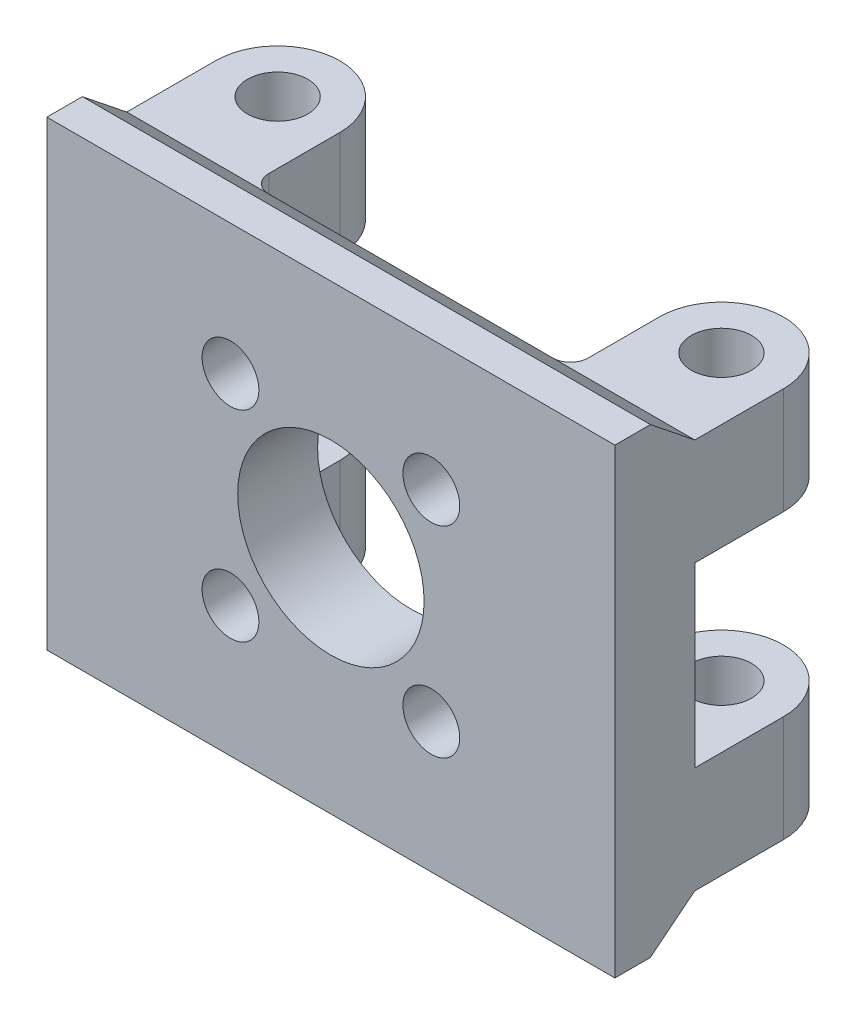
SolidWorks part; units mm, degrees
ref_plane "前视基准面" through (0, 0, 0) normal (0, 0, 1) x (1, 0, 0)
ref_plane "上视基准面" through (0, 0, 0) normal (0, 1, 0) x (1, 0, 0)
ref_plane "右视基准面" through (0, 0, 0) normal (1, 0, 0) x (0, 0, -1)
other "Configuration Table"
ref_plane "基准面1" through (0, 0, 0) normal (0, 0, -1) x (-1, 0, 0)
sketch "草图1" plane through (0, 0, 0) normal (0, 0, -1) x (-1, 0, 0)
  line L0 (16, 11) -> (-16, 11)
  line L1 (-16, 11) -> (-16, -11)
  line L2 (-16, -11) -> (16, -11)
  line L3 (16, -11) -> (16, 11)
extrude "凸台-拉伸1" add sketch "草图1" against normal blind 2.5
ref_plane "基准面2" through (0, 11, 0) normal (0, 1, 0) x (1, 0, 0)
sketch "草图2" plane through (0, 11, 0) normal (0, 1, 0) x (1, 0, 0)
  line L0 (9, 5) -> (9, 1)
  line L1 (8, 0) -> (16, 0)
  line L2 (16, 0) -> (16, 5)
  arc A0 (16, 5) -> (9, 5) centre (12.5, 5) ccw
  arc A1 (9, 1) -> (8, 0) centre (8, 1) cw
extrude "凸台-拉伸2" add sketch "草图2" against normal blind 6
sketch "草图3" plane through (0, 11, 0) normal (0, 1, 0) x (1, 0, 0)
  line L0 (-16, 0) -> (-8, 0)
  line L1 (-9, 1) -> (-9, 5)
  line L2 (-16, 5) -> (-16, 0)
  arc A0 (-8, 0) -> (-9, 1) centre (-8, 1) cw
  arc A1 (-9, 5) -> (-16, 5) centre (-12.5, 5) ccw
extrude "凸台-拉伸3" add sketch "草图3" against normal blind 6
ref_plane "基准面3" through (0, -11, 0) normal (0, -1, 0) x (1, 0, 0)
sketch "草图4" plane through (0, -11, 0) normal (0, -1, 0) x (1, 0, 0)
  line L0 (-8, 0) -> (-16, 0)
  line L1 (-16, 0) -> (-16, -5)
  line L2 (-9, -5) -> (-9, -1)
  arc A0 (-16, -5) -> (-9, -5) centre (-12.5, -5) ccw
  arc A1 (-9, -1) -> (-8, 0) centre (-8, -1) cw
extrude "凸台-拉伸4" add sketch "草图4" against normal blind 6
sketch "草图5" plane through (0, -11, 0) normal (0, -1, 0) x (1, 0, 0)
  line L0 (16, -5) -> (16, 0)
  line L1 (16, 0) -> (8, 0)
  line L2 (9, -1) -> (9, -5)
  arc A0 (9, -5) -> (16, -5) centre (12.5, -5) ccw
  arc A1 (8, 0) -> (9, -1) centre (8, -1) cw
extrude "凸台-拉伸5" add sketch "草图5" against normal blind 6
hole_wizard "Ø3.4 (3.4) 直径孔1" positions "草图7" profile "草图6" hole size "Ø3.4" standard "ANSI Metric"
sketch "草图7" plane through (0, -5, 0) normal (0, 1, 0) x (1, 0, 0)
  point P0 (-12.5, 5)
sketch "草图6" plane through (-12.5, -5, -5) normal (1, 0, 0) x (0, 0, 1)
  line L0 (0, 0) -> (0, 6)
  line L1 (0, 6) -> (1.7, 6)
  line L2 (1.7, 6) -> (1.7, 0)
  line L5 (1.7, 0) -> (0, 0)
  line L11 (0, -6.35) -> (0, 107.95) construction
  dimension "通孔孔直径" = 3.4
  dimension "通孔孔深度" = 6
hole_wizard "Ø3.4 (3.4) 直径孔2" positions "草图9" profile "草图8" hole size "Ø3.4" standard "ANSI Metric"
sketch "草图9" plane through (0, -11, 0) normal (0, -1, 0) x (-1, 0, 0)
  point P0 (-12.5, 5)
sketch "草图8" plane through (12.5, -11, -5) normal (1, 0, 0) x (0, 0, -1)
  line L0 (0, 0) -> (0, 6)
  line L1 (0, 6) -> (1.7, 6)
  line L2 (1.7, 6) -> (1.7, 0)
  line L5 (1.7, 0) -> (0, 0)
  line L11 (0, -6.35) -> (0, 107.95) construction
  dimension "通孔孔直径" = 3.4
  dimension "通孔孔深度" = 6
hole_wizard "Ø3.4 (3.4) 直径孔3" positions "草图11" profile "草图10" hole size "Ø3.4" standard "ANSI Metric"
sketch "草图11" plane through (0, 5, 0) normal (0, -1, 0) x (-1, 0, 0)
  point P0 (12.5, 5)
sketch "草图10" plane through (-12.5, 5, -5) normal (1, 0, 0) x (0, 0, -1)
  line L0 (0, 0) -> (0, 6)
  line L1 (0, 6) -> (1.7, 6)
  line L2 (1.7, 6) -> (1.7, 0)
  line L5 (1.7, 0) -> (0, 0)
  line L11 (0, -6.35) -> (0, 107.95) construction
  dimension "通孔孔直径" = 3.4
  dimension "通孔孔深度" = 6
hole_wizard "Ø3.4 (3.4) 直径孔4" positions "草图13" profile "草图12" hole size "Ø3.4" standard "ANSI Metric"
sketch "草图13" plane through (0, 11, 0) normal (0, 1, 0) x (1, 0, 0)
  point P0 (12.5, 5)
sketch "草图12" plane through (12.5, 11, -5) normal (1, 0, 0) x (0, 0, 1)
  line L0 (0, 0) -> (0, 22)
  line L1 (0, 22) -> (1.7, 22)
  line L2 (1.7, 22) -> (1.7, 0)
  line L5 (1.7, 0) -> (0, 0)
  line L11 (0, -6.35) -> (0, 107.95) construction
  dimension "通孔孔直径" = 3.4
  dimension "通孔孔深度" = 22
hole_wizard "Ø3.2 (3.2) 直径孔1" positions "草图15" profile "草图14" hole size "Ø3.2" standard "ANSI Metric"
sketch "草图15" plane through (0, 0, 0) normal (0, 0, -1) x (-1, 0, 0)
  point P0 (5.6569, 5.6569)
  point P1 (-5.6569, 5.6569)
  point P2 (-5.6569, -5.6569)
  point P3 (5.6569, -5.6569)
sketch "草图14" plane through (-5.6569, 5.6569, 0) normal (1, 0, 0) x (0, 1, 0)
  line L0 (0, 0) -> (0, 2.5)
  line L1 (0, 2.5) -> (1.6, 2.5)
  line L2 (1.6, 2.5) -> (1.6, 0)
  line L5 (1.6, 0) -> (0, 0)
  line L11 (0, -6.35) -> (0, 107.95) construction
  dimension "通孔孔直径" = 3.2
  dimension "通孔孔深度" = 2.5
hole_wizard "Ø10.5 (10.5) 直径孔1" positions "草图17" profile "草图16" hole size "Ø10.5" standard "ANSI Metric"
sketch "草图17" plane through (0, 0, 0) normal (0, 0, -1) x (-1, 0, 0)
  point P0 (0, 0)
sketch "草图16" plane through (0, 0, 0) normal (1, 0, 0) x (0, 1, 0)
  line L0 (0, 0) -> (0, 2.5)
  line L1 (0, 2.5) -> (5.25, 2.5)
  line L2 (5.25, 2.5) -> (5.25, 0)
  line L5 (5.25, 0) -> (0, 0)
  line L11 (0, -6.35) -> (0, 107.95) construction
  dimension "通孔孔直径" = 10.5
  dimension "通孔孔深度" = 2.5
sketch "草图18" plane through (0, 0, 2.5) normal (0, 0, 1) x (1, 0, 0)
  line L0 (-16, 11) -> (-16, 13)
  line L1 (-16, 13) -> (16, 13)
  line L2 (16, 13) -> (16, 11)
  line L3 (16, -11) -> (16, -13)
  line L4 (-16, 11) -> (-16, -11)
  line L5 (-16, -11) -> (16, -11)
  line L6 (16, -11) -> (16, 11)
  line L7 (16, 11) -> (-16, 11)
  line L8 (-16, 11) -> (-16, -11)
  line L10 (16, -11) -> (16, 11)
  line L12 (16, -13) -> (-16, -13)
  line L13 (-16, -13) -> (-16, -11)
  circle A0 centre (-5.6569, 5.6569) radius 1.6
  circle A1 centre (5.6569, 5.6569) radius 1.6
  circle A2 centre (5.6569, -5.6569) radius 1.6
  circle A3 centre (-5.6569, -5.6569) radius 1.6
  circle A4 centre (0, 0) radius 5.25
  dimension "D2" = 2
  dimension "D3" = 2
  dimension "D1" = 0
extrude "凸台-拉伸7" add sketch "草图18" along normal blind 2
ref_plane "基准面4" through (-16, -11, 2.5) normal (-1, 0, 0) x (0, 0, 1)
sketch "草图20" plane through (-16, -11, 2.5) normal (-1, 0, 0) x (0, 0, 1)
  line L0 (0, -2) -> (-2.5, 0)
rib "筋1" sketch "草图20" sketch "草图20" thickness 32 extrusion direction parallel to sketch draft on no parameters "D1"=32
ref_plane "基准面5" through (16, 11, 2.5) normal (1, 0, 0) x (0, 0, -1)
sketch "草图22" plane through (16, 11, 2.5) normal (1, 0, 0) x (0, 0, -1)
  line L0 (0, 2) -> (2.5, 0)
  line L1 (3.875, 0) -> (1.125, 0) construction
rib "筋2" sketch "草图22" sketch "草图22" thickness 32 extrusion direction parallel to sketch draft on no parameters "D1"=32
